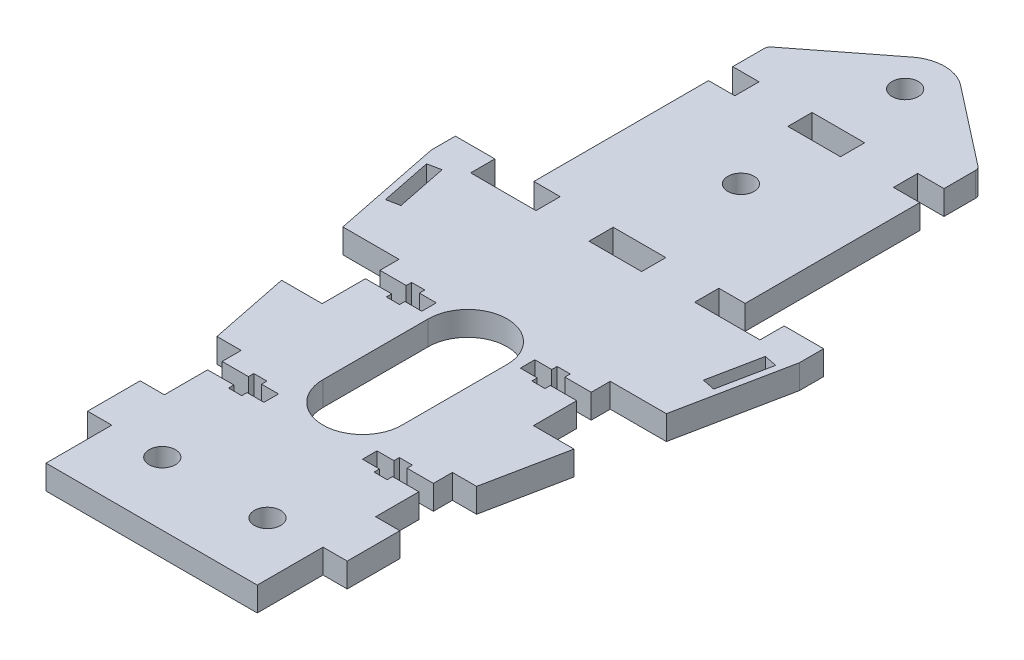
SolidWorks part; units mm, degrees
ref_plane "Front Plane" through (0, 0, 0) normal (0, 0, 1) x (1, 0, 0)
ref_plane "Top Plane" through (0, 0, 0) normal (0, 1, 0) x (1, 0, 0)
ref_plane "Right Plane" through (0, 0, 0) normal (1, 0, 0) x (0, 0, -1)
sketch "Sketch1" plane through (0, 0, 0) normal (0, 1, 0) x (1, 0, 0)
  line L0 (0, 96.7012) -> (0, 26.7242) construction
  line L1 (31.75, 26.7242) -> (25.5, 26.7242)
  line L2 (25.5, -85.217) -> (25.5, -69.342)
  line L3 (-25.5, -69.9464) -> (25.5, -69.9464) construction
  line L4 (0, 26.7242) -> (0, -69.9464) construction
  line L5 (25.5, -88.9) -> (-25.5, 88.9) construction
  line L6 (25.5, 88.9) -> (-25.5, -88.9) construction
  line L7 (-25.5, 77.6512) -> (25.5, 77.6512) construction
  line L8 (-25.5, -85.217) -> (-25.5, -69.342)
  line L9 (-25.5, 88.9) -> (-5.8561, 104.2134)
  line L10 (-25.5, 80.5722) -> (-25.5, 88.9)
  line L11 (5.8561, 104.2134) -> (25.5, 88.9)
  line L12 (-19.15, 74.7302) -> (-25.5, 74.7302)
  line L13 (-19.15, 74.7302) -> (-19.15, 80.5722)
  line L14 (-19.15, 80.5722) -> (-25.5, 80.5722)
  line L15 (19.15, 74.7302) -> (25.5, 74.7302)
  line L16 (-19.15, 74.7302) -> (-25.5, 80.5722) construction
  line L17 (-19.15, 80.5722) -> (-25.5, 74.7302) construction
  line L18 (6.35, 74.7302) -> (-6.35, 74.7302)
  line L19 (6.35, 74.7302) -> (6.35, 80.5722)
  line L20 (6.35, 80.5722) -> (-6.35, 80.5722)
  line L21 (-6.35, 74.7302) -> (-6.35, 80.5722)
  line L22 (6.35, 74.7302) -> (-6.35, 80.5722) construction
  line L23 (6.35, 80.5722) -> (-6.35, 74.7302) construction
  line L24 (19.15, 74.7302) -> (19.15, 80.5722)
  line L25 (19.15, 80.5722) -> (25.5, 80.5722)
  line L26 (25.5, 80.5722) -> (25.5, 88.9)
  line L27 (0, -69.9464) -> (0, -88.9) construction
  line L28 (0, -69.9464) -> (0, 26.7242) construction
  line L29 (0, -8.9111) -> (0, -34.3111) construction
  line L30 (9.525, -8.9111) -> (9.525, -34.3111)
  line L31 (-9.525, -8.9111) -> (-9.525, -34.3111)
  line L32 (-25.5, 53.6482) -> (25.5, 53.6482) construction
  line L33 (19.15, 32.5662) -> (25.5, 32.5662)
  line L34 (19.15, 32.5662) -> (19.15, 26.7242)
  line L35 (19.15, 26.7242) -> (25.5, 26.7242)
  line L36 (6.35, 32.5662) -> (6.35, 26.7242)
  line L37 (6.35, 32.5662) -> (-6.35, 32.5662)
  line L38 (6.35, 26.7242) -> (-6.35, 26.7242)
  line L39 (-6.35, 32.5662) -> (-6.35, 26.7242)
  line L40 (-19.15, 26.7242) -> (-25.5, 26.7242)
  line L41 (-19.15, 32.5662) -> (-19.15, 26.7242)
  line L42 (-19.15, 32.5662) -> (-25.5, 32.5662)
  line L43 (-25.5, 32.5662) -> (-25.5, 74.7302)
  line L44 (25.5, 32.5662) -> (25.5, 74.7302)
  line L45 (-44.45, 32.5662) -> (-34.925, 32.5662)
  line L46 (-31.75, 26.7242) -> (-25.5, 26.7242)
  line L47 (-44.45, 32.5662) -> (-44.45, 26.7242)
  line L48 (-25.5, -38.1) -> (-31.342, -38.1)
  line L49 (-34.925, 32.5662) -> (-34.925, 26.7242)
  line L50 (-44.45, 32.5662) -> (-31.75, 26.7242) construction
  line L51 (-44.45, 26.7242) -> (-31.75, 32.5662) construction
  line L52 (-31.342, -38.1) -> (-35.2968, -18.542)
  line L53 (-31.342, 0) -> (-39.0461, 0)
  line L54 (-31.342, -69.342) -> (-25.5, -69.342)
  line L55 (-31.342, -69.342) -> (-31.342, -56.642)
  line L56 (-31.342, -56.642) -> (-25.5, -56.642)
  line L57 (-25.5, -85.217) -> (25.5, -85.217)
  line L58 (-31.342, -69.342) -> (-25.5, -56.642) construction
  line L59 (-31.342, -56.642) -> (-25.5, -69.342) construction
  line L60 (-31.342, 0) -> (-25.5, 0)
  line L61 (-39.0461, 0) -> (-44.45, 26.7242)
  line L62 (-31.342, -18.542) -> (-25.5, -18.542)
  line L63 (-25.5, 0) -> (-25.5, -18.542)
  line L64 (-31.342, 0) -> (-25.5, -18.542) construction
  line L65 (-31.342, -18.542) -> (-25.5, 0) construction
  line L66 (-31.342, -18.542) -> (-35.2968, -18.542)
  line L67 (-25.5, -56.642) -> (-25.5, -38.1)
  line L68 (31.342, 0) -> (25.5, 0)
  line L69 (31.342, -18.542) -> (25.5, -18.542)
  line L70 (25.5, -38.1) -> (31.342, -38.1)
  line L71 (31.342, -69.342) -> (25.5, -69.342)
  line L72 (31.342, -56.642) -> (25.5, -56.642)
  line L73 (44.45, 32.5662) -> (44.45, 26.7242)
  line L74 (44.45, 32.5662) -> (34.925, 32.5662)
  line L75 (31.342, -18.542) -> (35.2968, -18.542)
  line L76 (39.0461, 0) -> (44.45, 26.7242)
  line L77 (31.342, -69.342) -> (31.342, -56.642)
  line L78 (31.342, 0) -> (39.0461, 0)
  line L79 (31.342, -38.1) -> (35.2968, -18.542)
  line L80 (34.925, 32.5662) -> (34.925, 26.7242)
  line L81 (34.925, 26.7242) -> (31.75, 26.7242)
  line L83 (25.5, -18.542) -> (25.5, 0)
  line L84 (25.5, -56.642) -> (25.5, -38.1)
  line L85 (-34.925, 26.7242) -> (-31.75, 26.7242)
  circle A0 centre (0, 96.7012) radius 3.175
  circle A1 centre (0, 57.0536) radius 3.175
  arc A4 (5.8561, 104.2134) -> (-5.8561, 104.2134) centre (0, 96.7012) ccw
  circle A5 centre (-12.7, -69.9464) radius 3.175
  circle A6 centre (12.7, -69.9464) radius 3.175
  arc A7 (9.525, -8.9111) -> (-9.525, -8.9111) centre (0, -8.9111) ccw
  arc A8 (-9.525, -34.3111) -> (9.525, -34.3111) centre (0, -34.3111) ccw
  point P0 (0, 0)
  point P14 (-38.1, 29.6452)
  point P17 (-6.35, 29.6452)
  point P21 (-22.325, 77.6512)
  point P28 (0, 77.6512)
  point P45 (0, -21.6111)
  point P66 (-28.421, -62.992)
  point P72 (-28.421, -9.271)
  point P97 (28.421, -9.271)
  point P98 (28.421, -62.992)
  point P99 (38.1, 29.6452)
  dimension "D3" = 6.35
  dimension "D4" = 6.35
  dimension "D5" = 39.6476
  dimension "D6" = 12.7
  dimension "D7" = 5.842
  dimension "D8" = 38.1
  dimension "D9" = 19.05
  dimension "D10" = 19.05
  dimension "D15" = 6.35
  dimension "D17" = 9.525
  dimension "D1" = 51
  dimension "D2" = 177.8
  dimension "D11" = 5.842
  dimension "D12" = 6.35
  dimension "D13" = 12.7
  dimension "D14" = 50.8
  dimension "D16" = 12.7
  dimension "D18" = 21.082
  dimension "D19" = 5.842
  dimension "D20" = 5.842
  dimension "D21" = 12.7
  dimension "D22" = 18.542
  dimension "D23" = 5.842
  dimension "D24" = 18.542
  dimension "D25" = 38.1
  dimension "D26" = 15.875
  dimension "D27" = 9.525
  dimension "D28" = 127
extrude "Boss-Extrude1" add sketch "Sketch1" along normal blind 5.842
sketch "Sketch2" plane through (0, 5.842, 0) normal (0, 1, 0) x (1, 0, 0)
  line L0 (0, 26.7242) -> (0, -85.217) construction
  line L1 (-6.35, 26.7242) -> (6.35, 26.7242) construction
  line L2 (-25.5, -85.217) -> (25.5, -85.217) construction
  line L3 (-25.5, -6.35) -> (25.5, -6.35) construction
  line L4 (-25.5, 0) -> (-25.5, -18.542) construction
  line L5 (25.5, -18.542) -> (25.5, 0) construction
  line L6 (-25.5, -44.45) -> (25.5, -44.45) construction
  line L7 (-25.5, -38.1) -> (-25.5, -56.642) construction
  line L8 (25.5, -56.642) -> (25.5, -38.1) construction
  line L9 (-39.0461, 0) -> (-25.5, 0) construction
  line L10 (-31.342, -38.1) -> (-25.5, -38.1) construction
  line L11 (-15.975, -42.6974) -> (-15.975, -41.402)
  line L12 (-19.15, -46.2026) -> (-25.5, -46.2026)
  line L13 (-1.3648, -6.35) -> (-1.3648, -44.45) construction
  line L14 (-19.15, -42.6974) -> (-25.5, -42.6974)
  line L15 (-25.5, -46.2026) -> (-25.5, -42.6974)
  line L16 (-19.15, -46.2026) -> (-25.5, -42.6974) construction
  line L17 (-19.15, -42.6974) -> (-25.5, -46.2026) construction
  line L18 (-15.975, -47.498) -> (-19.15, -47.498)
  line L19 (-15.975, -47.498) -> (-15.975, -46.2026)
  line L20 (-15.975, -41.402) -> (-19.15, -41.402)
  line L21 (-19.15, -47.498) -> (-19.15, -46.2026)
  line L22 (-15.975, -47.498) -> (-19.15, -41.402) construction
  line L23 (-15.975, -41.402) -> (-19.15, -47.498) construction
  line L24 (-11.892, -46.2026) -> (-15.975, -46.2026)
  line L25 (-11.892, -46.2026) -> (-11.892, -42.6974)
  line L26 (-11.892, -42.6974) -> (-15.975, -42.6974)
  line L27 (-19.15, -42.6974) -> (-19.15, -41.402)
  line L28 (-11.892, -46.2026) -> (-15.975, -42.6974) construction
  line L29 (-11.892, -42.6974) -> (-15.975, -46.2026) construction
  line L30 (-1.3648, -25.4) -> (0, -25.4) construction
  line L31 (-11.892, -8.1026) -> (-15.975, -4.5974) construction
  line L32 (-11.892, -4.5974) -> (-15.975, -8.1026) construction
  line L33 (-15.975, -9.398) -> (-19.15, -3.302) construction
  line L34 (-15.975, -3.302) -> (-19.15, -9.398) construction
  line L35 (-19.15, -8.1026) -> (-25.5, -4.5974) construction
  line L36 (-19.15, -4.5974) -> (-25.5, -8.1026) construction
  line L37 (-19.15, -8.1026) -> (-19.15, -9.398)
  line L38 (-11.892, -8.1026) -> (-15.975, -8.1026)
  line L39 (-11.892, -4.5974) -> (-11.892, -8.1026)
  line L40 (-11.892, -4.5974) -> (-15.975, -4.5974)
  line L41 (-19.15, -3.302) -> (-19.15, -4.5974)
  line L42 (-15.975, -9.398) -> (-19.15, -9.398)
  line L43 (-15.975, -3.302) -> (-15.975, -4.5974)
  line L44 (-15.975, -3.302) -> (-19.15, -3.302)
  line L45 (-25.5, -4.5974) -> (-25.5, -8.1026)
  line L46 (-19.15, -8.1026) -> (-25.5, -8.1026)
  line L47 (-19.15, -4.5974) -> (-25.5, -4.5974)
  line L48 (-15.975, -8.1026) -> (-15.975, -9.398)
  line L49 (19.15, -4.5974) -> (25.5, -8.1026) construction
  line L50 (19.15, -8.1026) -> (25.5, -4.5974) construction
  line L51 (15.975, -3.302) -> (19.15, -9.398) construction
  line L52 (15.975, -9.398) -> (19.15, -3.302) construction
  line L53 (11.892, -4.5974) -> (15.975, -8.1026) construction
  line L54 (11.892, -8.1026) -> (15.975, -4.5974) construction
  line L55 (11.892, -42.6974) -> (15.975, -46.2026) construction
  line L56 (11.892, -46.2026) -> (15.975, -42.6974) construction
  line L57 (15.975, -41.402) -> (19.15, -47.498) construction
  line L58 (15.975, -47.498) -> (19.15, -41.402) construction
  line L59 (19.15, -42.6974) -> (25.5, -46.2026) construction
  line L60 (19.15, -46.2026) -> (25.5, -42.6974) construction
  line L61 (15.975, -8.1026) -> (15.975, -9.398)
  line L62 (19.15, -4.5974) -> (25.5, -4.5974)
  line L63 (19.15, -8.1026) -> (25.5, -8.1026)
  line L64 (25.5, -4.5974) -> (25.5, -8.1026)
  line L65 (15.975, -3.302) -> (19.15, -3.302)
  line L66 (15.975, -3.302) -> (15.975, -4.5974)
  line L67 (15.975, -9.398) -> (19.15, -9.398)
  line L68 (19.15, -3.302) -> (19.15, -4.5974)
  line L69 (11.892, -4.5974) -> (15.975, -4.5974)
  line L70 (11.892, -4.5974) -> (11.892, -8.1026)
  line L71 (11.892, -8.1026) -> (15.975, -8.1026)
  line L72 (19.15, -8.1026) -> (19.15, -9.398)
  line L73 (19.15, -42.6974) -> (19.15, -41.402)
  line L74 (11.892, -42.6974) -> (15.975, -42.6974)
  line L75 (11.892, -46.2026) -> (11.892, -42.6974)
  line L76 (11.892, -46.2026) -> (15.975, -46.2026)
  line L77 (19.15, -47.498) -> (19.15, -46.2026)
  line L78 (15.975, -41.402) -> (19.15, -41.402)
  line L79 (15.975, -47.498) -> (15.975, -46.2026)
  line L80 (15.975, -47.498) -> (19.15, -47.498)
  line L81 (25.5, -46.2026) -> (25.5, -42.6974)
  line L82 (19.15, -42.6974) -> (25.5, -42.6974)
  line L83 (19.15, -46.2026) -> (25.5, -46.2026)
  line L84 (15.975, -42.6974) -> (15.975, -41.402)
  point P22 (-22.325, -44.45)
  point P27 (-17.5625, -44.45)
  point P32 (-13.9335, -44.45)
  point P53 (-13.9335, -6.35)
  point P54 (-17.5625, -6.35)
  point P55 (-22.325, -6.35)
  point P80 (22.325, -6.35)
  point P81 (17.5625, -6.35)
  point P82 (13.9335, -6.35)
  point P83 (13.9335, -44.45)
  point P84 (17.5625, -44.45)
  point P85 (22.325, -44.45)
  dimension "D1" = 6.35
  dimension "D2" = 6.35
  dimension "D3" = 3.5052
  dimension "D4" = 6.35
  dimension "D5" = 6.096
  dimension "D6" = 3.175
  dimension "D7" = 4.083
extrude "Cut-Extrude1" cut sketch "Sketch2" against normal through all
fillet "Fillet1" radius 1.5875 2 edges at (25.5, 2.921, -88.9) (-25.5, 2.921, -88.9)
sketch "Sketch3" plane through (0, 5.842, 0) normal (0, 1, 0) x (1, 0, 0)
  line L0 (-44.45, 26.7242) -> (44.45, 26.7242) construction
  line L2 (-41.2107, 26.7242) -> (-28.1027, -38.1) construction
  line L3 (-35.2968, -18.542) -> (-31.342, -38.1) construction
  line L4 (0, 26.7242) -> (0, -38.1) construction
  line L5 (-42.1375, 23.2976) -> (-39.6204, 10.8495)
  line L6 (-42.1375, 23.2976) -> (-39.0255, 23.9269)
  line L7 (-39.6204, 10.8495) -> (-36.5084, 11.4788)
  line L8 (-39.0255, 23.9269) -> (-36.5084, 11.4788)
  line L9 (-42.1375, 23.2976) -> (-36.5084, 11.4788) construction
  line L10 (-39.6204, 10.8495) -> (-39.0255, 23.9269) construction
  line L11 (-32.313, -5.214) -> (-37.0004, -6.1618) construction
  line L20 (32.313, -5.214) -> (37.0004, -6.1618) construction
  line L21 (39.6204, 10.8495) -> (39.0255, 23.9269) construction
  line L22 (42.1375, 23.2976) -> (36.5084, 11.4788) construction
  line L23 (41.2107, 26.7242) -> (28.1027, -38.1) construction
  line L28 (39.0255, 23.9269) -> (36.5084, 11.4788)
  line L29 (39.6204, 10.8495) -> (36.5084, 11.4788)
  line L30 (42.1375, 23.2976) -> (39.0255, 23.9269)
  line L31 (42.1375, 23.2976) -> (39.6204, 10.8495)
  point P15 (-39.3229, 17.3882)
  point P22 (-34.6567, -5.6879)
  point P40 (34.6567, -5.6879)
  point P41 (39.3229, 17.3882)
  dimension "D1" = 3.175
  dimension "D2" = 3.175
  dimension "D3" = 12.7
  dimension "D4" = 9.525
extrude "Cut-Extrude2" cut sketch "Sketch3" against normal through all
